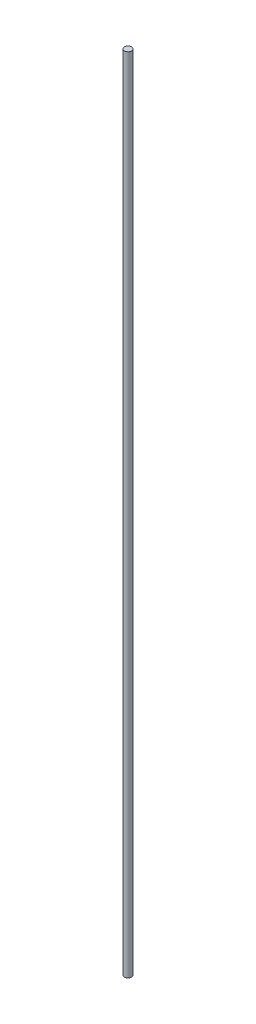
SolidWorks part; units mm, degrees
ref_plane "Front Plane" through (0, 0, 0) normal (0, 0, 1) x (1, 0, 0)
ref_plane "Top Plane" through (0, 0, 0) normal (0, 1, 0) x (1, 0, 0)
ref_plane "Right Plane" through (0, 0, 0) normal (1, 0, 0) x (0, 0, -1)
sketch "Sketch1" plane through (0, 0, 0) normal (0, 1, 0) x (1, 0, 0)
  circle A0 centre (0, 0) radius 4
extrude "Boss-Extrude1" add sketch "Sketch1" along normal blind 887.03
sketch "Sketch2" plane through (0, 887.03, 0) normal (0, 1, 0) x (1, 0, 0)
  circle A0 centre (0, 0) radius 4
extrude "Boss-Extrude2" add sketch "Sketch2" along normal blind 18
